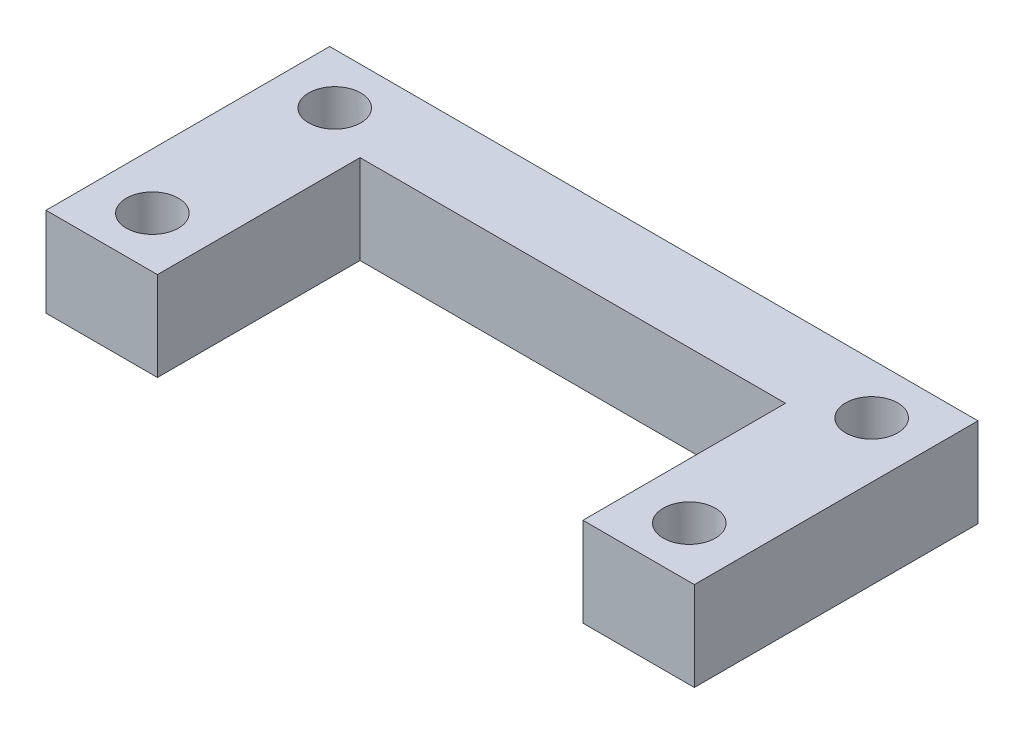
SolidWorks part; units mm, degrees
ref_plane "Front Plane" through (0, 0, 0) normal (0, 0, 1) x (1, 0, 0)
ref_plane "Top Plane" through (0, 0, 0) normal (0, 1, 0) x (1, 0, 0)
ref_plane "Right Plane" through (0, 0, 0) normal (1, 0, 0) x (0, 0, -1)
sketch "Sketch1" plane through (0, 0, 0) normal (0, 1, 0) x (1, 0, 0)
  line L1 (-20.32, 11.557) -> (20.32, 11.557)
  line L2 (-20.32, 11.557) -> (-20.32, -6.223)
  line L3 (-20.32, -6.223) -> (20.32, -6.223)
  line L4 (20.32, 11.557) -> (20.32, -6.223)
  dimension "D1" = 40.64
  dimension "D2" = 17.78
  dimension "D3" = 11.557
  dimension "D4" = 20.32
extrude "Boss-Extrude1" add sketch "Sketch1" along normal blind 29.972
sketch "Sketch2" plane through (0, 0, 6.223) normal (0, 0, 1) x (1, 0, 0)
  line L0 (-20.32, 29.972) -> (20.32, 29.972) construction
  line L1 (-13.335, 29.972) -> (13.335, 29.972)
  line L2 (-13.335, 29.972) -> (-13.335, 0)
  line L3 (-13.335, 0) -> (13.335, 0)
  line L4 (13.335, 29.972) -> (13.335, 0)
  line L5 (-20.32, 0) -> (20.32, 0) construction
  line L6 (-20.32, 29.972) -> (-20.32, 0) construction
  line L7 (20.32, 29.972) -> (20.32, 0) construction
  dimension "D1" = 6.985
  dimension "D2" = 6.985
extrude "Cut-Extrude1" cut sketch "Sketch2" against normal blind 12.7
sketch "Sketch5" plane through (0, 0, -11.557) normal (0, 0, -1) x (-1, 0, 0)
  circle A0 centre (0, 15.875) radius 8.001
  dimension "D1" = 16.002
extrude "Cut-Extrude4" cut sketch "Sketch5" against normal through all
sketch "Sketch6" plane through (-20.32, 0, 0) normal (-1, 0, 0) x (0, 0, 1)
  line L1 (6.223, 29.972) -> (6.223, 0) construction
  circle A0 centre (-2.667, 15.24) radius 1.1303
  dimension "D1" = 2.2606
  dimension "D3" = 8.89
extrude "Cut-Extrude5" cut sketch "Sketch6" against normal through all
sketch "Sketch7" plane through (0, 0, -6.477) normal (0, 0, 1) x (1, 0, 0)
  line L1 (-9.9502, 29.9815) -> (9.9502, 29.9815)
  line L2 (-9.9502, 29.9815) -> (-9.9502, 25.405)
  line L3 (-9.9502, 25.405) -> (9.9502, 25.405)
  line L4 (9.9502, 29.9815) -> (9.9502, 25.405)
extrude "Boss-Extrude2" add sketch "Sketch7" along normal blind 5.08
hole_wizard "5/32 (0.15625) Diameter Hole1" positions "Sketch10" profile "Sketch9" hole size "5/32" standard "Ansi Inch" end condition through all
sketch "Sketch10" plane through (0, 0, -11.557) normal (0, 0, -1) x (-1, 0, 0)
  point P0 (-10.16, 21.717)
  point P1 (-10.16, 10.033)
  point P3 (10.16, 21.717)
  point P5 (10.16, 10.033)
sketch "Sketch9" plane through (10.16, 21.717, -11.557) normal (1, 0, 0) x (0, 1, 0)
  line L0 (0, 0) -> (0, 17.78)
  line L1 (0, 17.78) -> (1.9844, 17.78)
  line L2 (1.9844, 17.78) -> (1.9844, 0)
  line L5 (1.9844, 0) -> (0, 0)
  line L11 (0, -6.35) -> (0, 107.95) construction
  dimension "Thru Hole Dia." = 3.9688
  dimension "Thru Hole Depth" = 17.78
hole_wizard "#30 (0.1285) Diameter Hole1" positions "Sketch13" profile "Sketch12" hole size "#30" standard "Ansi Inch" end condition through all
sketch "Sketch13" plane through (0, 29.972, 0) normal (0, 1, 0) x (-1, 0, 0)
  line L0 (-20.32, -11.557) -> (20.32, -11.557) construction
  line L1 (20.32, -11.557) -> (20.32, 6.223) construction
  line L2 (-20.32, 6.223) -> (-20.32, -11.557) construction
  line L3 (20.32, 6.223) -> (13.335, 6.223) construction
  line L4 (-13.335, 6.223) -> (-20.32, 6.223) construction
  point P0 (16.8275, 3.048)
  point P1 (16.8275, -8.382)
  point P3 (-16.8275, -8.382)
  point P5 (-16.8275, 3.048)
  point P20 (16.8275, 6.223)
  point P24 (-16.8275, 6.223)
  dimension "D1" = 3.175
  dimension "D2" = 3.4925
  dimension "D3" = 3.175
  dimension "D4" = 3.4925
  dimension "D5" = 3.175
  dimension "D6" = 3.175
  dimension "D7" = 3.4925
  dimension "D8" = 3.4925
sketch "Sketch12" plane through (-16.8275, 29.972, 3.048) normal (1, 0, 0) x (0, 0, 1)
  line L0 (0, 0) -> (0, 29.972)
  line L1 (0, 29.972) -> (1.6319, 29.972)
  line L2 (1.6319, 29.972) -> (1.6319, 0)
  line L5 (1.6319, 0) -> (0, 0)
  line L11 (0, -6.35) -> (0, 107.95) construction
  dimension "Thru Hole Dia." = 3.2639
  dimension "Thru Hole Depth" = 29.972
hole_wizard "#4-40 Tapped Hole1" positions "Sketch15" profile "Sketch14" tap size "#4-40" standard "Ansi Inch"
sketch "Sketch15" plane through (0, 29.972, 0) normal (0, 1, 0) x (-1, 0, 0)
  line L0 (-20.32, 6.223) -> (-20.32, -11.557) construction
  line L1 (-9.9502, -1.397) -> (9.9502, -1.397) construction
  point P0 (0, -3.937)
  point P2 (-20.32, -2.667)
  point P5 (0, -1.397)
  dimension "D1" = 20.32
  dimension "D2" = 2.54
sketch "Sketch14" plane through (0, 29.972, -3.937) normal (1, 0, 0) x (0, 0, 1)
  line L0 (0, 0) -> (0, 29.972)
  line L1 (0, 29.972) -> (1.1303, 29.972)
  line L2 (1.1303, 29.972) -> (1.1303, 0)
  line L5 (1.1303, 0) -> (0, 0)
  line L11 (0, -6.35) -> (0, 107.95) construction
  dimension "Thru Tap Drill Dia." = 2.2606
  dimension "Thru Tap Drill Depth" = 29.972
cosmetic thread "Hole Thread1" parameters "D2"=2.8448
sketch "Sketch16" plane through (0, 0, -11.557) normal (0, 0, -1) x (-1, 0, 0)
  line L0 (20.32, 29.972) -> (20.32, 0) construction
  line L1 (-20.32, 32.2176) -> (20.32, 32.2176)
  line L2 (-20.32, 32.2176) -> (-20.32, 5.588)
  line L3 (-20.32, 5.588) -> (20.32, 5.588)
  line L4 (20.32, 32.2176) -> (20.32, 5.588)
  line L5 (-20.32, 0) -> (20.32, 0) construction
  dimension "D1" = 5.588
  dimension "D2" = 26.6296
extrude "Cut-Extrude6" cut sketch "Sketch16" against normal through all
